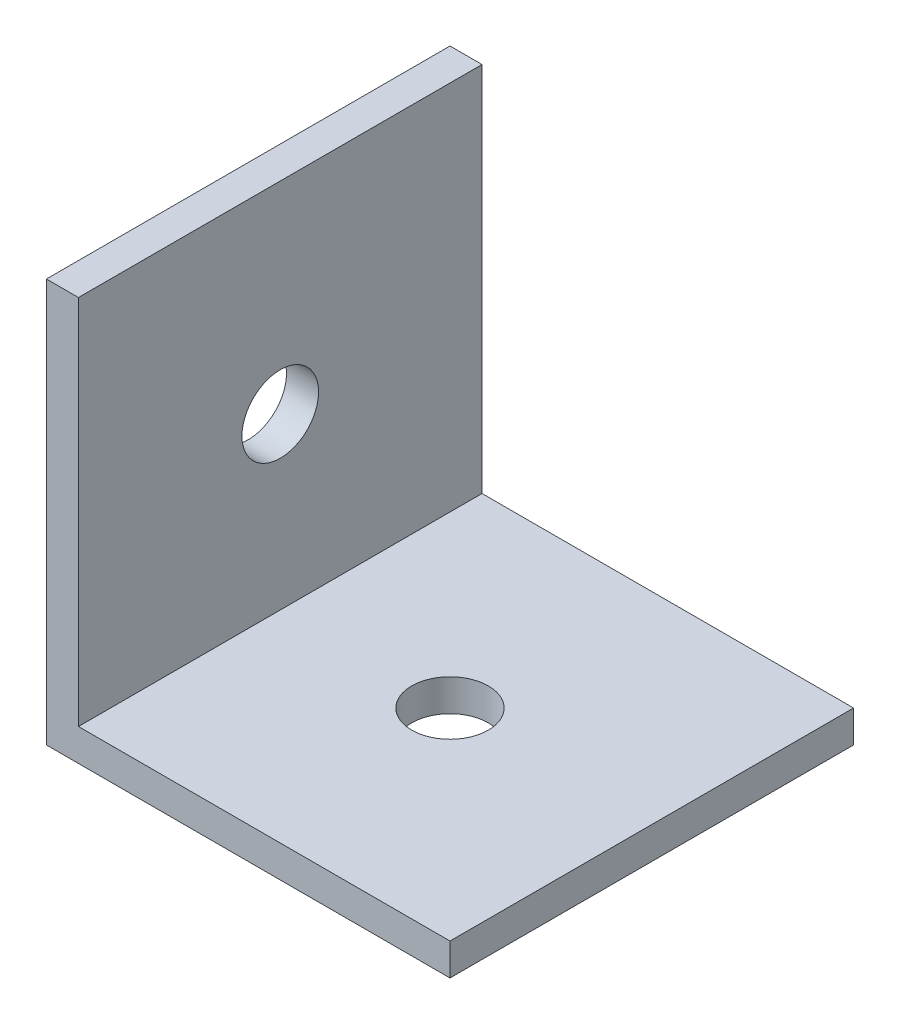
SolidWorks part; units mm, degrees
ref_plane "Front Plane" through (0, 0, 0) normal (0, 0, 1) x (1, 0, 0)
ref_plane "Top Plane" through (0, 0, 0) normal (0, 1, 0) x (1, 0, 0)
ref_plane "Right Plane" through (0, 0, 0) normal (1, 0, 0) x (0, 0, -1)
sketch "Sketch1" plane through (0, 0, 0) normal (0, 0, 1) x (1, 0, 0)
  line L0 (0, 20) -> (0, 0)
  line L1 (0, 0) -> (20, 0)
  line L2 (1.5875, 20) -> (1.5875, 1.5875)
  line L3 (1.5875, 1.5875) -> (20, 1.5875)
  line L4 (0, 20) -> (1.5875, 20)
  line L5 (20, 1.5875) -> (20, 0)
  dimension "D1" = 20
  dimension "D2" = 1.5875
extrude "Boss-Extrude1" add sketch "Sketch1" along normal mid plane 20
hole_wizard "#6 Clearance Hole1" positions "Sketch3" profile "Sketch2" hole size "#6" standard "ANSI Inch"
sketch "Sketch3" plane through (0, 0, 0) normal (0, -1, 0) x (-1, 0, 0)
  line L0 (0, 0) -> (-20, 0) construction
  line L1 (-20, -10) -> (-20, 10) construction
  point P0 (-10, 0)
sketch "Sketch2" plane through (10, 0, 0) normal (1, 0, 0) x (0, 0, -1)
  line L0 (0, 0) -> (0, 21.1418)
  line L1 (0, 21.1418) -> (1.8986, 20.001)
  line L2 (1.8986, 20.001) -> (1.8986, 0)
  line L5 (1.8986, 0) -> (0, 0)
  line L10 (0, 21.1418) -> (-1.8987, 20.001) construction
  line L11 (0, -6.35) -> (0, 107.95) construction
  dimension "Hole Dia." = 3.7973
  dimension "Hole Depth" = 20.001
  dimension "Drill Angle" = 118
hole_wizard "#6 Clearance Hole2" positions "Sketch5" profile "Sketch4" hole size "#6" standard "ANSI Inch"
sketch "Sketch5" plane through (0, 0, 0) normal (-1, 0, 0) x (0, 0, 1)
  line L0 (0, 0) -> (0, 20) construction
  line L1 (10, 20) -> (-10, 20) construction
  point P0 (0, 10)
sketch "Sketch4" plane through (0, 10, 0) normal (0, 1, 0) x (0, 0, 1)
  line L0 (0, 0) -> (0, 2.7273)
  line L1 (0, 2.7273) -> (1.8986, 1.5865)
  line L2 (1.8986, 1.5865) -> (1.8986, 0)
  line L5 (1.8986, 0) -> (0, 0)
  line L10 (0, 2.7273) -> (-1.8987, 1.5865) construction
  line L11 (0, -6.35) -> (0, 107.95) construction
  dimension "Hole Dia." = 3.7973
  dimension "Hole Depth" = 1.5865
  dimension "Drill Angle" = 118
